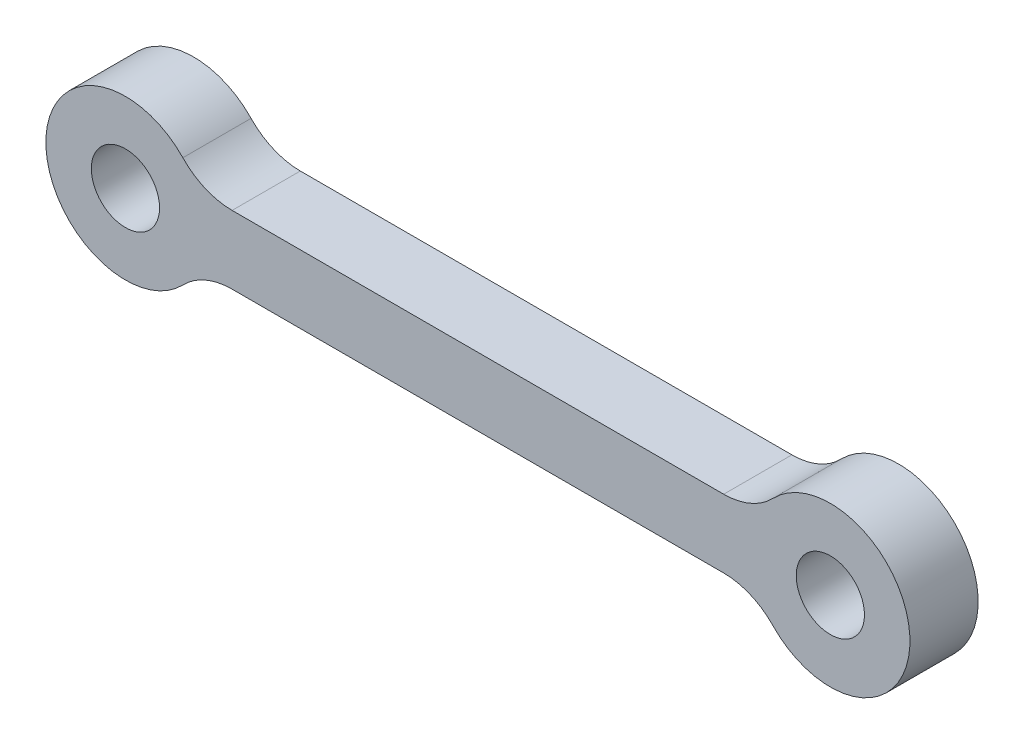
SolidWorks part; units mm, degrees
material "Wrought Stainless Steel"
ref_plane "Front Plane" through (0, 0, 0) normal (0, 0, 1) x (1, 0, 0)
ref_plane "Top Plane" through (0, 0, 0) normal (0, 1, 0) x (1, 0, 0)
ref_plane "Right Plane" through (0, 0, 0) normal (1, 0, 0) x (0, 0, -1)
sketch "Sketch1" plane through (0, 0, 0) normal (0, 0, 1) x (1, 0, 0)
  line L1 (15.5, -1.5) -> (-12.3377, -1.5)
  line L3 (12.3377, 1.5) -> (-12.3377, 1.5)
  line L5 (15.5, -1.5) -> (-15.5, 1.5) construction
  line L6 (15.5, 1.5) -> (-15.5, -1.5) construction
  arc A0 (-12.3377, 1.5) -> (-12.3377, -1.5) centre (-15.5, 0) ccw
  circle A1 centre (-15.5, 0) radius 1.5
  arc A2 (12.3377, -1.5) -> (12.3377, 1.5) centre (15.5, 0) ccw
  circle A3 centre (15.5, 0) radius 1.5
  point P6 (0, 0)
  dimension "D1" = 7
  dimension "D2" = 3
  dimension "D3" = 7
  dimension "D4" = 3
  dimension "D5" = 31
  dimension "D6" = 15.5
  dimension "D7" = 1.5
  dimension "D8" = 3
extrude "Boss-Extrude1" add sketch "Sketch1" along normal blind 3
fillet "Fillet1" radius 3 4 edges at (12.3377, 1.5, 1.5) (-12.3377, 1.5, 1.5) (12.3377, -1.5, 1.5) (-12.3377, -1.5, 1.5)
